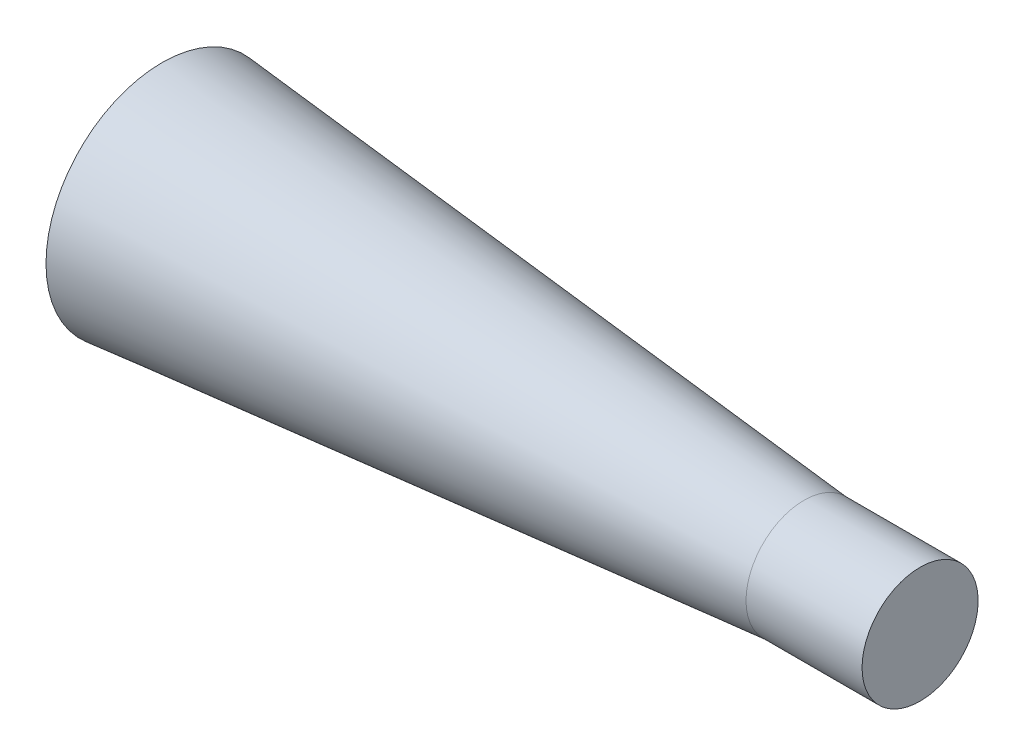
SolidWorks part; units mm, degrees
ref_plane "Front Plane" through (0, 0, 0) normal (0, 0, 1) x (1, 0, 0)
ref_plane "Top Plane" through (0, 0, 0) normal (0, 1, 0) x (1, 0, 0)
ref_plane "Right Plane" through (0, 0, 0) normal (1, 0, 0) x (0, 0, -1)
sketch "Sketch1" plane through (0, 0, 0) normal (0, 0, 1) x (1, 0, 0)
  line L0 (0, 0) -> (0, -14386.0926) construction
  line L1 (0, 0) -> (14386.0926, 0) construction
  line L2 (0, 0) -> (34, 0)
  line L3 (34, 0) -> (34, 2.5)
  line L4 (34, 2.5) -> (29, 2.5)
  line L5 (29, 2.5) -> (1.3397, 5)
  arc A0 (1.3397, 5) -> (1.3397, -5) centre (10, 0) ccw
  point P12 (0, 0)
  dimension "D3" = 10
  dimension "D1" = 5
  dimension "D2" = 10
  dimension "D4" = 5
  dimension "D5" = 34
revolve "Revolve2" add sketch "Sketch1" angle 360 about L1
